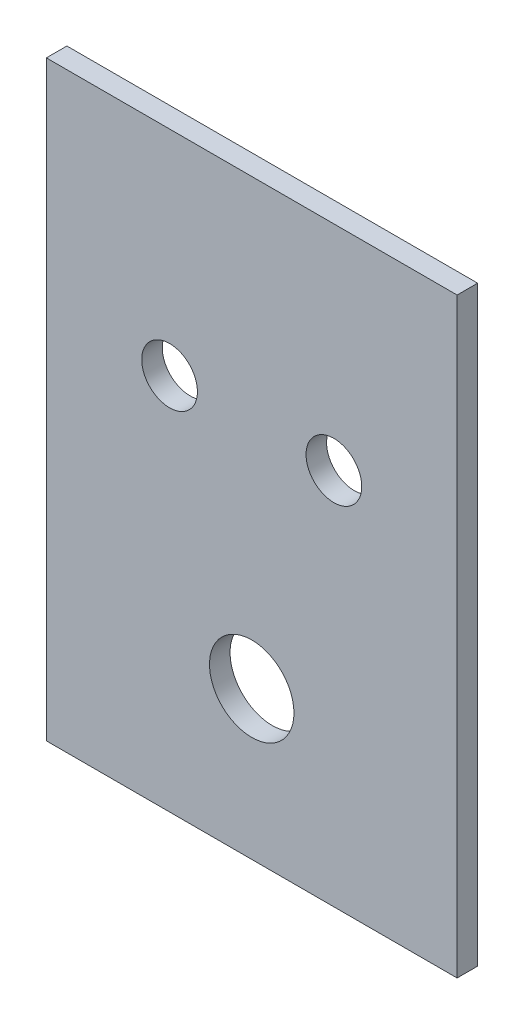
SolidWorks part; units mm, degrees
material "AISI 4130 Steel, annealed at 865C"
ref_plane "Front Plane" through (0, 0, 0) normal (0, 0, 1) x (1, 0, 0)
ref_plane "Top Plane" through (0, 0, 0) normal (0, 1, 0) x (1, 0, 0)
ref_plane "Right Plane" through (0, 0, 0) normal (1, 0, 0) x (0, 0, -1)
sketch "Sketch2" plane through (0, 0, 0) normal (0, 0, 1) x (1, 0, 0)
  line L0 (0, 35.56) -> (31.75, 35.56)
  line L1 (0, 0) -> (31.75, 0)
  line L2 (0, 0) -> (0, 45.72)
  line L3 (0, 45.72) -> (31.75, 45.72)
  line L4 (31.75, 0) -> (31.75, 45.72)
  line L5 (0, 22.86) -> (31.75, 22.86)
  circle A0 centre (9.525, 29.21) radius 2.1527
  circle A1 centre (22.225, 29.21) radius 2.1526
  circle A2 centre (15.875, 11.43) radius 3.2639
  point P14 (15.875, 45.72)
  dimension "D4" = 4.3053
  dimension "D5" = 10.16
  dimension "D11" = 6.5278
  dimension "D9" = 12.7
  dimension "D1" = 45.72
  dimension "D2" = 31.75
  dimension "D3" = 11.43
  dimension "D6" = 9.525
  dimension "D7" = 9.525
  dimension "D8" = 16.51
extrude "Boss-Extrude1" add sketch "Sketch2" along normal blind 1.5875
